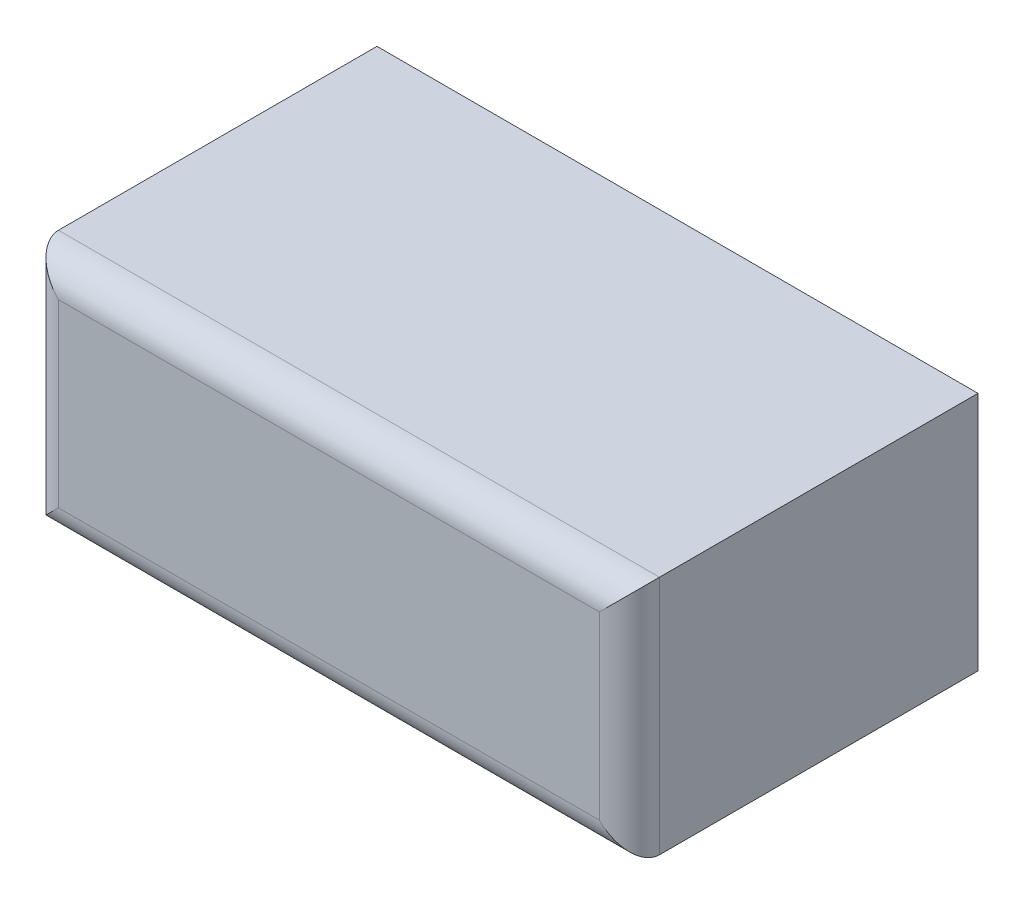
SolidWorks part; units mm, degrees
ref_plane "Front Plane" through (0, 0, 0) normal (0, 0, 1) x (1, 0, 0)
ref_plane "Top Plane" through (0, 0, 0) normal (0, 1, 0) x (1, 0, 0)
ref_plane "Right Plane" through (0, 0, 0) normal (1, 0, 0) x (0, 0, -1)
sketch "Sketch1" plane through (0, 0, 0) normal (0, 0, 1) x (1, 0, 0)
  line L1 (-25, 10) -> (25, 10)
  line L2 (-25, 10) -> (-25, 30)
  line L3 (-25, 30) -> (25, 30)
  line L4 (25, 10) -> (25, 30)
  line L5 (-25, 10) -> (25, 30) construction
  line L6 (-25, 30) -> (25, 10) construction
  point P0 (0, 20)
  dimension "D1" = 20
  dimension "D2" = 50
  dimension "D3" = 20
  dimension "D4" = 10
extrude "Boss-Extrude1" add sketch "Sketch1" along normal up to surface (29 mm away)
fillet "Fillet1" radius 2.5 4 edges at (25, 20, 29) (0, 30, 29) (-25, 20, 29) (0, 10, 29)
sketch "Sketch2" plane through (0, 10, 0) normal (0, -1, 0) x (-1, 0, 0)
  line L0 (25, -13.25) -> (-25, -13.25) construction
  line L1 (25, -26.5) -> (25, 0) construction
  line L2 (-25, -26.5) -> (-25, 0) construction
  text T0 "BATTERY"
extrude "Boss-Extrude2" add sketch "Sketch2" along normal blind 0.1
